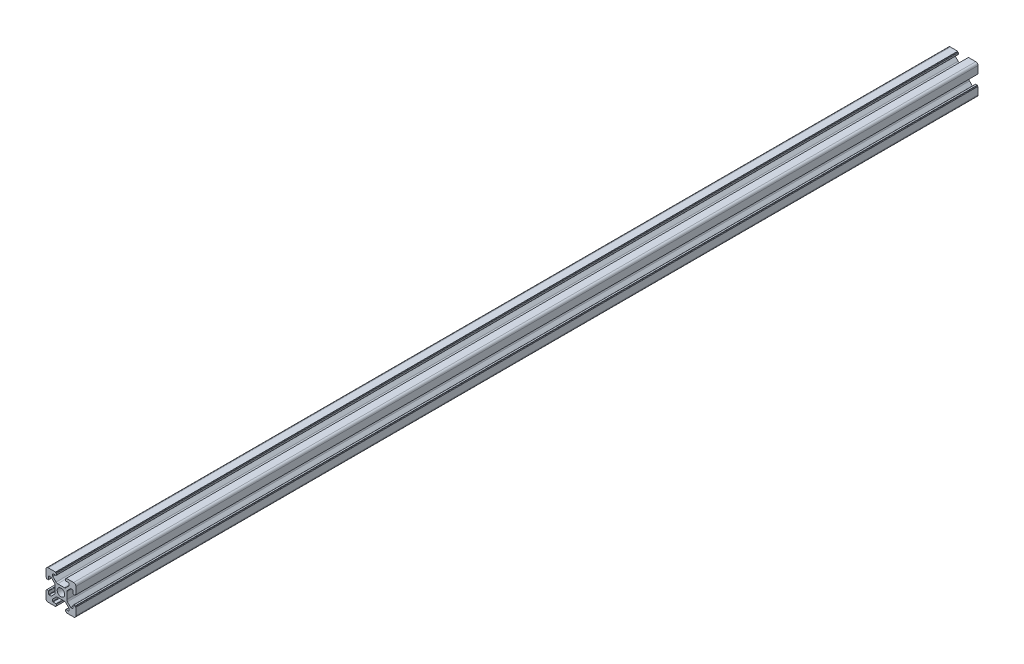
SolidWorks part; units mm, degrees
ref_plane "前视基准面" through (0, 0, 0) normal (0, 0, 1) x (1, 0, 0)
ref_plane "上视基准面" through (0, 0, 0) normal (0, 1, 0) x (1, 0, 0)
ref_plane "右视基准面" through (0, 0, 0) normal (1, 0, 0) x (0, 0, -1)
sketch "草图1" plane through (0, 0, 0) normal (0, 0, 1) x (1, 0, 0)
  line L0 (4.216, 3.2442) -> (6.4367, 5.4649)
  line L1 (6.4367, 5.4649) -> (7.7767, 5.4649)
  line L2 (8.0767, 5.1649) -> (8.0767, 3.3649)
  line L3 (8.3767, 3.0649) -> (9.3767, 3.0649)
  line L4 (9.3767, 3.0649) -> (9.3767, 3.3649)
  line L5 (9.5767, 3.5649) -> (9.8767, 3.5649)
  line L6 (9.8767, 3.5649) -> (9.8767, 8.4649)
  line L7 (8.3767, 9.9649) -> (3.4767, 9.9649)
  line L8 (3.4767, 9.9649) -> (3.4767, 9.6649)
  line L9 (3.2767, 9.4649) -> (2.9767, 9.4649)
  line L10 (2.9767, 9.4649) -> (2.9767, 8.4649)
  line L11 (3.2767, 8.1649) -> (5.0767, 8.1649)
  line L12 (5.3767, 7.8649) -> (5.3767, 6.5249)
  line L13 (5.3767, 6.5249) -> (3.156, 4.3042)
  line L14 (2.0953, 3.8649) -> (-2.342, 3.8649)
  line L15 (-3.4027, 4.3042) -> (-5.6233, 6.5249)
  line L16 (-5.6233, 6.5249) -> (-5.6233, 7.8649)
  line L17 (-5.3233, 8.1649) -> (-3.5233, 8.1649)
  line L18 (-3.2233, 8.4649) -> (-3.2233, 9.4649)
  line L19 (-3.2233, 9.4649) -> (-3.5233, 9.4649)
  line L20 (-3.7233, 9.6649) -> (-3.7233, 9.9649)
  line L21 (-3.7233, 9.9649) -> (-8.6233, 9.9649)
  line L22 (-10.1233, 8.4649) -> (-10.1233, 3.5649)
  line L23 (-10.1233, 3.5649) -> (-9.8233, 3.5649)
  line L24 (-9.6233, 3.3649) -> (-9.6233, 3.0649)
  line L25 (-9.6233, 3.0649) -> (-8.6233, 3.0649)
  line L26 (-8.3233, 3.3649) -> (-8.3233, 5.1649)
  line L27 (-8.0233, 5.4649) -> (-6.6833, 5.4649)
  line L28 (-6.6833, 5.4649) -> (-4.4627, 3.2442)
  line L29 (-4.0233, 2.1836) -> (-4.0233, -2.2538)
  line L30 (-4.4627, -3.3144) -> (-6.6833, -5.5351)
  line L31 (-6.6833, -5.5351) -> (-8.0233, -5.5351)
  line L32 (-8.3233, -5.2351) -> (-8.3233, -3.4351)
  line L33 (-8.6233, -3.1351) -> (-9.6233, -3.1351)
  line L34 (-9.6233, -3.1351) -> (-9.6233, -3.4351)
  line L35 (-9.8233, -3.6351) -> (-10.1233, -3.6351)
  line L36 (-10.1233, -3.6351) -> (-10.1233, -8.5351)
  line L37 (-8.6233, -10.0351) -> (-3.7233, -10.0351)
  line L38 (-3.7233, -10.0351) -> (-3.7233, -9.7351)
  line L39 (-3.5233, -9.5351) -> (-3.2233, -9.5351)
  line L40 (-3.2233, -9.5351) -> (-3.2233, -8.5351)
  line L41 (-3.5233, -8.2351) -> (-5.3233, -8.2351)
  line L42 (-5.6233, -7.9351) -> (-5.6233, -6.5951)
  line L43 (-5.6233, -6.5951) -> (-3.4027, -4.3744)
  line L44 (-2.342, -3.9351) -> (2.0953, -3.9351)
  line L45 (3.156, -4.3744) -> (5.3767, -6.5951)
  line L46 (5.3767, -6.5951) -> (5.3767, -7.9351)
  line L47 (5.0767, -8.2351) -> (3.2767, -8.2351)
  line L48 (2.9767, -8.5351) -> (2.9767, -9.5351)
  line L49 (2.9767, -9.5351) -> (3.2767, -9.5351)
  line L50 (3.4767, -9.7351) -> (3.4767, -10.0351)
  line L51 (3.4767, -10.0351) -> (8.3767, -10.0351)
  line L52 (9.8767, -8.5351) -> (9.8767, -3.6351)
  line L53 (9.8767, -3.6351) -> (9.5767, -3.6351)
  line L54 (9.3767, -3.4351) -> (9.3767, -3.1351)
  line L55 (9.3767, -3.1351) -> (8.3767, -3.1351)
  line L56 (8.0767, -3.4351) -> (8.0767, -5.2351)
  line L57 (7.7767, -5.5351) -> (6.4367, -5.5351)
  line L58 (6.4367, -5.5351) -> (4.216, -3.3144)
  line L59 (3.7767, -2.2538) -> (3.7767, 2.1836)
  circle A0 centre (-0.1233, -0.0351) radius 2.5
  arc A1 (8.0767, 5.1649) -> (7.7767, 5.4649) centre (7.7767, 5.1649) ccw
  arc A2 (8.0767, 3.3649) -> (8.3767, 3.0649) centre (8.3767, 3.3649) ccw
  arc A3 (9.5767, 3.5649) -> (9.3767, 3.3649) centre (9.5767, 3.3649) ccw
  arc A4 (9.8767, 8.4649) -> (8.3767, 9.9649) centre (8.3767, 8.4649) ccw
  arc A5 (3.2767, 9.4649) -> (3.4767, 9.6649) centre (3.2767, 9.6649) ccw
  arc A6 (2.9767, 8.4649) -> (3.2767, 8.1649) centre (3.2767, 8.4649) ccw
  arc A7 (5.3767, 7.8649) -> (5.0767, 8.1649) centre (5.0767, 7.8649) ccw
  arc A8 (2.0953, 3.8649) -> (3.156, 4.3042) centre (2.0953, 5.3649) ccw
  arc A9 (-3.4027, 4.3042) -> (-2.342, 3.8649) centre (-2.342, 5.3649) ccw
  arc A10 (-5.3233, 8.1649) -> (-5.6233, 7.8649) centre (-5.3233, 7.8649) ccw
  arc A11 (-3.5233, 8.1649) -> (-3.2233, 8.4649) centre (-3.5233, 8.4649) ccw
  arc A12 (-3.7233, 9.6649) -> (-3.5233, 9.4649) centre (-3.5233, 9.6649) ccw
  arc A13 (-8.6233, 9.9649) -> (-10.1233, 8.4649) centre (-8.6233, 8.4649) ccw
  arc A14 (-9.6233, 3.3649) -> (-9.8233, 3.5649) centre (-9.8233, 3.3649) ccw
  arc A15 (-8.6233, 3.0649) -> (-8.3233, 3.3649) centre (-8.6233, 3.3649) ccw
  arc A16 (-8.0233, 5.4649) -> (-8.3233, 5.1649) centre (-8.0233, 5.1649) ccw
  arc A17 (-4.0233, 2.1836) -> (-4.4627, 3.2442) centre (-5.5233, 2.1836) ccw
  arc A18 (-4.4627, -3.3144) -> (-4.0233, -2.2538) centre (-5.5233, -2.2538) ccw
  arc A19 (-8.3233, -5.2351) -> (-8.0233, -5.5351) centre (-8.0233, -5.2351) ccw
  arc A20 (-8.3233, -3.4351) -> (-8.6233, -3.1351) centre (-8.6233, -3.4351) ccw
  arc A21 (-9.8233, -3.6351) -> (-9.6233, -3.4351) centre (-9.8233, -3.4351) ccw
  arc A22 (-10.1233, -8.5351) -> (-8.6233, -10.0351) centre (-8.6233, -8.5351) ccw
  arc A23 (-3.5233, -9.5351) -> (-3.7233, -9.7351) centre (-3.5233, -9.7351) ccw
  arc A24 (-3.2233, -8.5351) -> (-3.5233, -8.2351) centre (-3.5233, -8.5351) ccw
  arc A25 (-5.6233, -7.9351) -> (-5.3233, -8.2351) centre (-5.3233, -7.9351) ccw
  arc A26 (-2.342, -3.9351) -> (-3.4027, -4.3744) centre (-2.342, -5.4351) ccw
  arc A27 (3.156, -4.3744) -> (2.0953, -3.9351) centre (2.0953, -5.4351) ccw
  arc A28 (5.0767, -8.2351) -> (5.3767, -7.9351) centre (5.0767, -7.9351) ccw
  arc A29 (3.2767, -8.2351) -> (2.9767, -8.5351) centre (3.2767, -8.5351) ccw
  arc A30 (3.4767, -9.7351) -> (3.2767, -9.5351) centre (3.2767, -9.7351) ccw
  arc A31 (8.3767, -10.0351) -> (9.8767, -8.5351) centre (8.3767, -8.5351) ccw
  arc A32 (9.3767, -3.4351) -> (9.5767, -3.6351) centre (9.5767, -3.4351) ccw
  arc A33 (8.3767, -3.1351) -> (8.0767, -3.4351) centre (8.3767, -3.4351) ccw
  arc A34 (7.7767, -5.5351) -> (8.0767, -5.2351) centre (7.7767, -5.2351) ccw
  arc A35 (3.7767, -2.2538) -> (4.216, -3.3144) centre (5.2767, -2.2538) ccw
  arc A36 (4.216, 3.2442) -> (3.7767, 2.1836) centre (5.2767, 2.1836) ccw
extrude "凸台-拉伸1" add sketch "草图1" along normal blind 604
